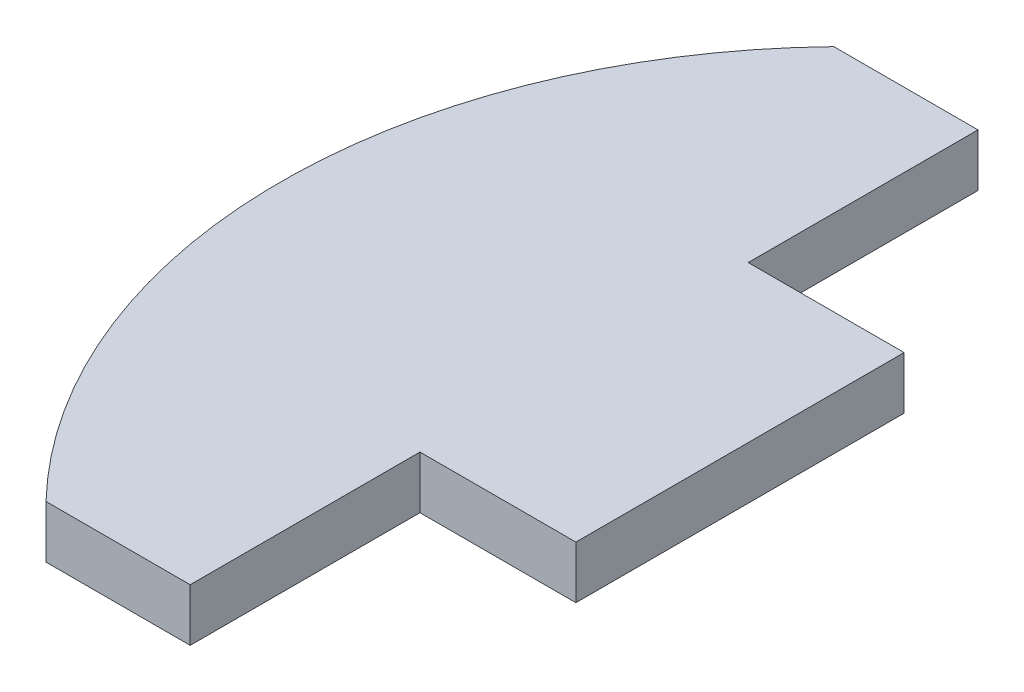
SolidWorks part; units mm, degrees
ref_plane "Front Plane" through (0, 0, 0) normal (0, 0, 1) x (1, 0, 0)
ref_plane "Top Plane" through (0, 0, 0) normal (0, 1, 0) x (1, 0, 0)
ref_plane "Right Plane" through (0, 0, 0) normal (1, 0, 0) x (0, 0, -1)
sketch "Sketch1" plane through (0, 0, 0) normal (0, 1, 0) x (1, 0, 0)
  line L0 (-12.392, 12) -> (-8, 12)
  line L1 (-8, 12) -> (-8, 5)
  line L2 (-8, 5) -> (-3.25, 5)
  line L3 (-3.25, 5) -> (-3.25, -5)
  line L4 (-17.25, 0) -> (-3.25, 0) construction
  line L5 (-8, -5) -> (-3.25, -5)
  line L6 (-8, -12) -> (-8, -5)
  line L7 (-12.392, -12) -> (-8, -12)
  line L8 (-12.392, 12) -> (-8, 12)
  arc A0 (-12.392, 12) -> (-12.392, -12) centre (0, 0) ccw
  point P12 (-3.25, 0)
  dimension "D1" = 34.5
  dimension "D3" = 8
  dimension "D2" = 12
  dimension "D4" = 5
  dimension "D5" = 3.25
extrude "Boss-Extrude1" add sketch "Sketch1" along normal blind 1.6 contours L4 A0 L7 L6 L5 L3 | A0 L4 L3 L2 L1 L0
